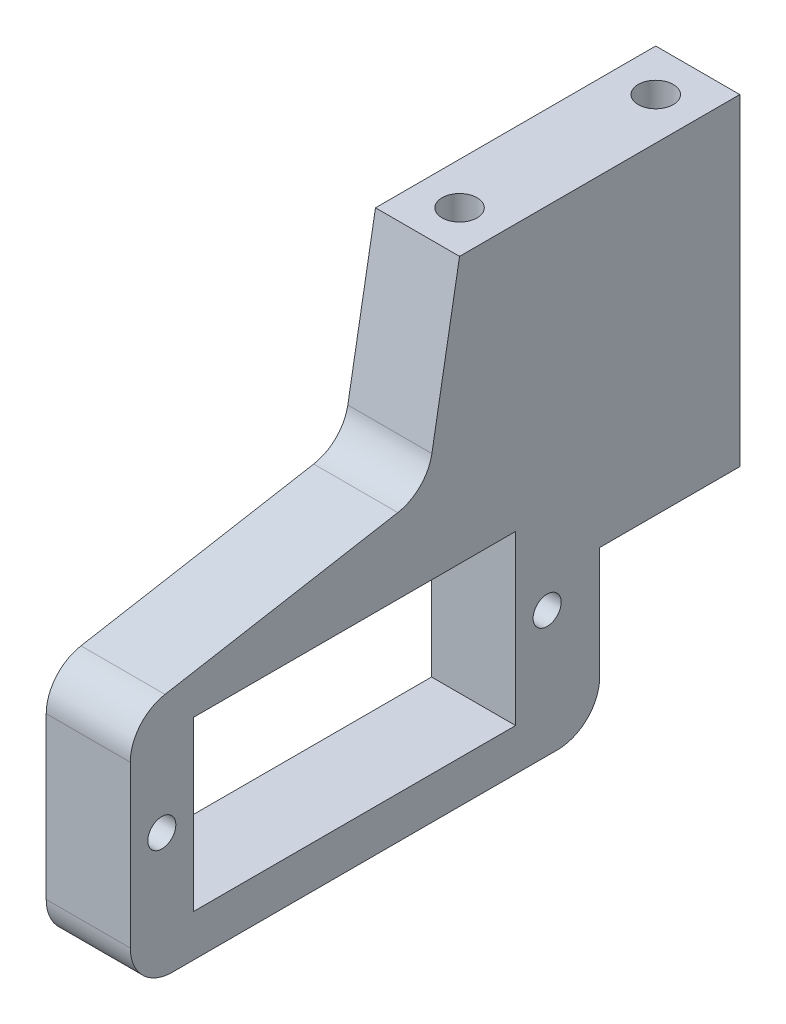
SolidWorks part; units mm, degrees
ref_plane "Front Plane" through (0, 0, 0) normal (0, 0, 1) x (1, 0, 0)
ref_plane "Top Plane" through (0, 0, 0) normal (0, 1, 0) x (1, 0, 0)
ref_plane "Right Plane" through (0, 0, 0) normal (1, 0, 0) x (0, 0, -1)
sketch "Sketch2" plane through (0, 0, 0) normal (1, 0, 0) x (0, 0, -1)
  line L0 (-16, -31) -> (-39, -31)
  line L1 (-20, 0) -> (-22.3397, -13.2689)
  line L2 (-22.3397, -13.2689) -> (-43.5, -17)
  line L8 (0, -34) -> (0, 0)
  line L9 (-43.5, -34) -> (0, -34)
  line L10 (-16, -19) -> (-16, -31)
  line L11 (-39, -19) -> (-16, -19)
  line L12 (-39, -31) -> (-39, -19)
  line L14 (-43.5, -17) -> (-43.5, -34)
  line L16 (0, 0) -> (-20, 0)
  circle A2 centre (-41.25, -25) radius 1
  circle A3 centre (-13.75, -25) radius 1
  dimension "D8" = 20
  dimension "D9" = 6
  dimension "D11" = 2
  dimension "D1" = 19
  dimension "D2" = 39
  dimension "D3" = 3
  dimension "D4" = 2.25
  dimension "D5" = 2.25
  dimension "D6" = 4.5
  dimension "D7" = 12
  dimension "D10" = 23
  dimension "D12" = 100
  dimension "D13" = 100
  dimension "D14" = 2
extrude "Boss-Extrude1" add sketch "Sketch2" along normal blind 6
sketch "Sketch3" plane through (0, 0, 0) normal (-1, 0, 0) x (0, 0, 1)
  line L1 (0, -34) -> (10, -34)
  line L2 (0, -34) -> (0, -23)
  line L3 (0, -23) -> (10, -23)
  line L4 (10, -34) -> (10, -23)
  dimension "D1" = 10
  dimension "D2" = 11
extrude "Cut-Extrude1" cut sketch "Sketch3" against normal up to next
fillet "Fillet1" radius 3 4 edges at (3, -13.2689, 22.3397) (3, -34, 10) (3, -34, 43.5) (3, -17, 43.5)
hole_wizard "Tap Drill for M3x0.5 Tap1" positions "3DSketch1" profile "Sketch4" hole size "M3x0.5" standard "ANSI Metric"
sketch3d "3DSketch1"
  line L0 (6, -23, 0) -> (0, -23, 0) construction
  line L1 (6, -23, 10) -> (6, -23, 0) construction
  line L2 (0, 0, 0) -> (0, 0, 20) construction
  line L3 (6, 0, 0) -> (0, 0, 0) construction
  line L4 (6, 0, 20) -> (0, 0, 20) construction
  point P0 (3, 0, 3)
  point P2 (3, 0, 17)
  point P4 (3, -23, 5)
  dimension "D1" = 5
  dimension "D2" = 3
  dimension "D3" = 3
  dimension "D4" = 3
  dimension "D5" = 3
  dimension "D6" = 3
sketch "Sketch4" plane through (3, 0, 3) normal (1, 0, 0) x (0, 0, 1)
  line L0 (0, 0) -> (0, 10.7511)
  line L1 (0, 10.7511) -> (1.25, 10)
  line L2 (1.25, 10) -> (1.25, 0)
  line L5 (1.25, 0) -> (0, 0)
  line L10 (0, 10.7511) -> (-1.25, 10) construction
  line L11 (0, -6.35) -> (0, 107.95) construction
  dimension "Hole Dia." = 2.5
  dimension "Hole Depth" = 10
  dimension "Drill Angle" = 118
